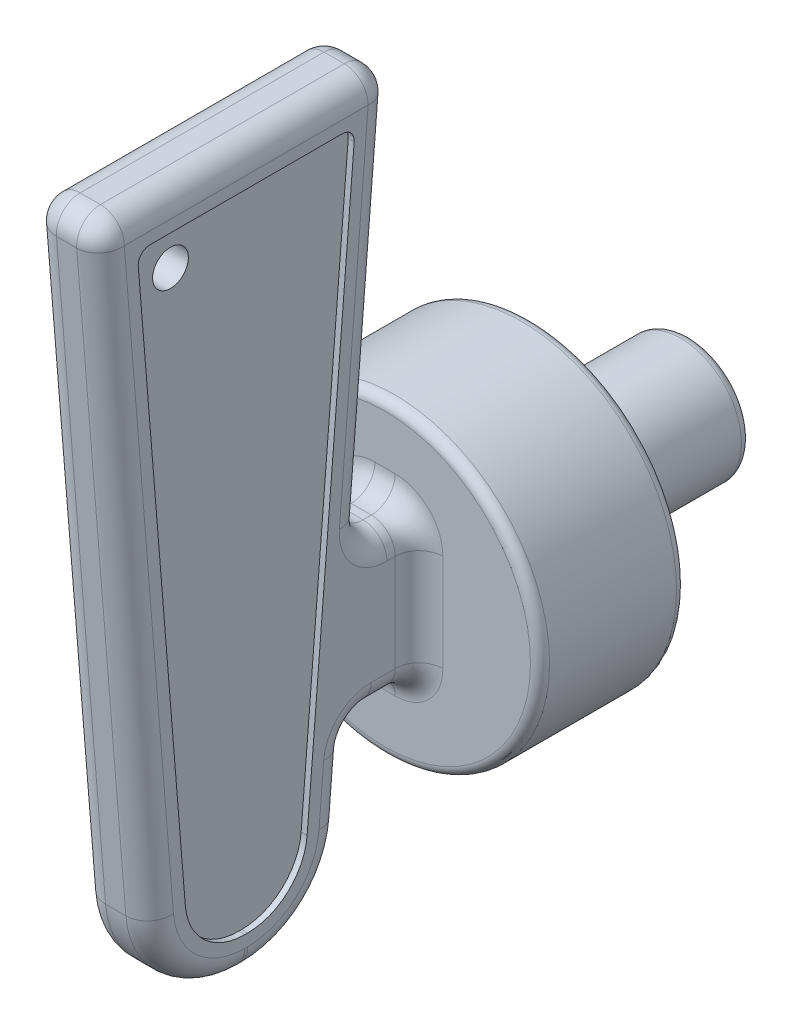
SolidWorks part; units mm, degrees
material "Custom Plastic"
ref_plane "X-Y Datum" through (0, 0, 0) normal (0, 0, 1) x (1, 0, 0)
ref_plane "X-Z Datum" through (0, 0, 0) normal (0, 1, 0) x (1, 0, 0)
ref_plane "Y-Z Datum" through (0, 0, 0) normal (1, 0, 0) x (0, 0, -1)
sketch "Sketch1" plane through (0, 0, 0) normal (0, 0, 1) x (1, 0, 0)
  circle A0 centre (0, 0) radius 13
  dimension "D1" = 26
extrude "Boss-Extrude1" add sketch "Sketch1" along normal blind 12.25
shell "Shell1" thickness 2
sketch "Sketch2" plane through (0, 0, 10.25) normal (0, 0, -1) x (-1, 0, 0)
  circle A1 centre (0, 0) radius 5.1
  dimension "D1" = 10.2
extrude "Boss-Extrude2" add sketch "Sketch2" along normal blind 23.6
sketch "Sketch3" plane through (0, 0, 0) normal (1, 0, 0) x (0, 0, -1)
  line L0 (-12.25, 13) -> (-12.25, -13) construction
  line L1 (-12.25, 13) -> (-12.25, -13)
  line L2 (-12.25, 6.075) -> (-12.25, -6.075)
  line L3 (-26.75, 40) -> (-26.75, -20.1) construction
  line L4 (-12.25, 6.075) -> (-17.1159, 6.075)
  line L5 (-12.25, 6.075) -> (-12.25, -6.075)
  line L6 (-12.25, -6.075) -> (-18.1065, -6.075)
  line L8 (-39.15, 40) -> (-14.35, 40)
  line L9 (-34.25, -20.1) -> (-19.25, -20.1)
  line L10 (-39.15, 40) -> (-34.25, -20.1)
  line L11 (-19.25, -20.1) -> (-14.35, 40)
  line L12 (0, 13) -> (-12.25, 13) construction
  line L13 (0, 13) -> (-12.25, 13)
  point P5 (-12.25, 0)
  point P8 (-25.9114, 21.5485)
  point P13 (-26.75, 40)
  point P16 (-26.75, -20.1)
  point P17 (-24.1174, -29.1478)
  point P18 (-16.6203, 40.5623)
  point P20 (-17.1159, 6.075)
  point P21 (-18.1065, -6.075)
  dimension "D1" = 12.15
  dimension "D2" = 24.8
  dimension "D3" = 15
  dimension "D4" = 60.1
  dimension "D5" = 27
  dimension "D6" = 14.5
extrude "Boss-Extrude3" add sketch "Sketch3" along normal mid plane 5.7 contours L11 L6 L1 L4 | L8 L3 L9 L11 | L3 L8 L10 L9
ref_plane "Plane1" through (0, -5.1, 0) normal (0, -1, 0) x (-1, 0, 0)
sketch "Sketch4" plane through (0, -5.1, 0) normal (0, -1, 0) x (-1, 0, 0)
  line L0 (5.1, 13.35) -> (-5.1, 13.35) construction
  circle A0 centre (0, 4.85) radius 2
  point P2 (0, 5.7209)
  point P3 (0, 0)
  point P5 (0, 5.647)
  dimension "D1" = 4
  dimension "D2" = 8.5
extrude "Boss-Extrude4" add sketch "Sketch4" along normal blind 4 and the other way up to surface other way up to face at (-5.1, 0, -13.35)
fillet "Fillet1" radius 0.8 1 edges at (0, -9.1, -6.85)
fillet "Fillet2" radius 0.8 3 edges at (-5.1, 0, -13.35) (13, 0, 0) (13, 0, 12.25)
fillet "Fillet3" radius 8 2 edges at (0, -20.1, 34.25) (0, -20.1, 19.25)
fillet "Fillet4" radius 2 2 edges at (0, 40, 39.15) (0, 40, 14.35)
fillet "Fillet5" radius 2 28 edges at (2.85, 12.5437, 36.9115) (-2.85, 12.5437, 36.9115) (2.85, -17.9822, 32.2978) (-2.85, -17.9822, 32.2978) (2.85, 39.3555, 38.4509) (-2.85, 39.3555, 38.4509) (2.85, -20.1, 26.75) (-2.85, -20.1, 26.75) (-2.85, 40, 26.75) (2.85, 40, 26.75) (2.85, -17.9822, 21.2022) (-2.85, -17.9822, 21.2022) (2.85, 39.3555, 15.0491) (-2.85, 39.3555, 15.0491) (2.85, -9.4125, 18.3786) (-2.85, -9.4125, 18.3786) (-2.85, 0, 12.25) (2.85, 0, 12.25) (2.85, 21.9562, 15.8211) (-2.85, 21.9562, 15.8211) (0, -6.075, 18.1065) (-2.85, -6.075, 15.1783) (2.85, -6.075, 15.1783) (0, -6.075, 12.25) (0, 6.075, 12.25) (-2.85, 6.075, 14.683) (2.85, 6.075, 14.683) (0, 6.075, 17.1159)
sketch "Sketch5" plane through (2.85, 0, 0) normal (1, 0, 0) x (0, 0, -1)
  line L8 (-19.9297, 8.4813) -> (-21.2464, -7.6687)
  line L16 (-21.6408, -12.5063) -> (-21.2464, -7.6687)
  line L17 (-16.263, -3.075) -> (-15.25, -3.075)
  line L18 (-15.25, -3.075) -> (-15.25, 3.0842)
  line L19 (-19.9297, 8.4813) -> (-17.6045, 37)
  line L20 (-17.6045, 37) -> (-35.8955, 37)
  line L21 (-35.8955, 37) -> (-31.8592, -12.5063)
  line L22 (-26.8757, -17.1) -> (-26.6243, -17.1)
  line L23 (-21.6408, -12.5063) -> (-21.2464, -7.6687)
  line L24 (-16.263, -3.075) -> (-15.25, -3.075)
  line L25 (-15.25, -3.075) -> (-15.25, 3.0842)
  line L26 (-19.9297, 8.4813) -> (-17.6045, 37)
  line L27 (-17.6045, 37) -> (-35.8955, 37)
  line L28 (-35.8955, 37) -> (-31.8592, -12.5063)
  line L29 (-26.8757, -17.1) -> (-26.6243, -17.1)
  arc A8 (-26.6243, -17.1) -> (-21.6408, -12.5063) centre (-26.6243, -12.1) ccw
  arc A9 (-16.263, -3.075) -> (-21.2464, -7.6687) centre (-16.263, -8.075) ccw
  arc A10 (-19.9297, 8.4813) -> (-15.25, 3.0842) centre (-14.9462, 8.075) ccw
  arc A11 (-31.8592, -12.5063) -> (-26.8757, -17.1) centre (-26.8757, -12.1) ccw
  arc A12 (-26.6243, -17.1) -> (-21.6408, -12.5063) centre (-26.6243, -12.1) ccw
  arc A13 (-16.263, -3.075) -> (-21.2464, -7.6687) centre (-16.263, -8.075) ccw
  arc A14 (-19.9297, 8.4813) -> (-15.25, 3.0842) centre (-14.9462, 8.075) ccw
  arc A15 (-31.8592, -12.5063) -> (-26.8757, -17.1) centre (-26.8757, -12.1) ccw
  dimension "D1" = 1
extrude "Cut-Extrude1" cut sketch "Sketch5" against normal blind 0.5 contours L28 A15 L29 A12 L23 L8 L26 L27
fillet "Fillet6" radius 1 2 edges at (2.6, 37, 17.6045) (2.6, 37, 35.8955)
mirror "Mirror1" about plane through (0, 0, 0) normal (1, 0, 0) of "Fillet6", "Cut-Extrude1"
sketch "Sketch6" plane through (2.35, 0, 0) normal (1, 0, 0) x (0, 0, -1)
  line L0 (-35.5459, 36.6778) -> (-32.6048, 33.9667)
  circle A0 centre (-32.6048, 33.9667) radius 1.5
  arc A3 (-34.8106, 37) -> (-35.8073, 35.9187) centre (-34.8106, 36) ccw construction
  point P7 (-33.6887, 34.8759)
  dimension "D2" = 3
  dimension "D1" = 4
extrude "Cut-Extrude2" cut sketch "Sketch6" against normal through all
